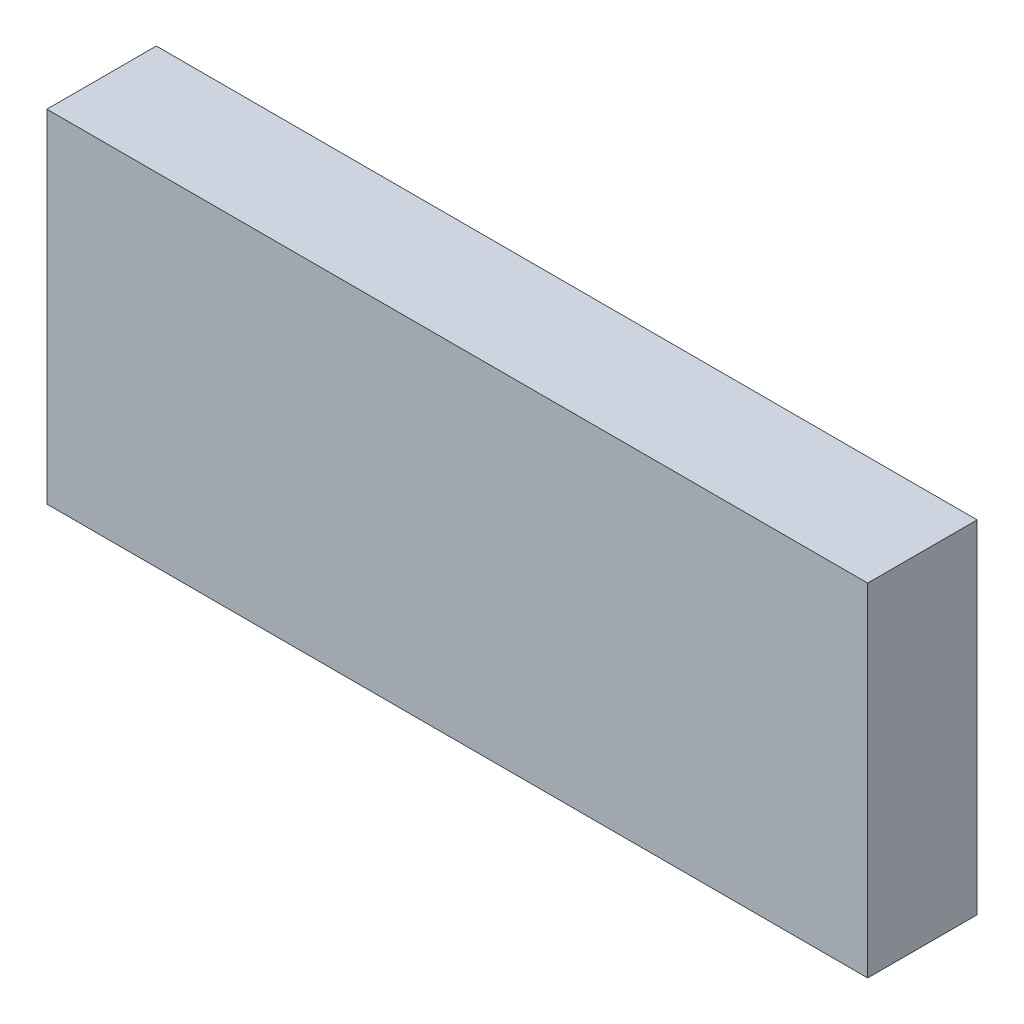
SolidWorks part; units mm, degrees
ref_plane "Front Plane" through (0, 0, 0) normal (0, 0, 1) x (1, 0, 0)
ref_plane "Top Plane" through (0, 0, 0) normal (0, 1, 0) x (1, 0, 0)
ref_plane "Right Plane" through (0, 0, 0) normal (1, 0, 0) x (0, 0, -1)
sketch "Sketch1" plane through (0, 0, 0) normal (0, 0, 1) x (1, 0, 0)
  line L1 (-90, -37.5) -> (90, -37.5)
  line L2 (-90, -37.5) -> (-90, 37.5)
  line L3 (-90, 37.5) -> (90, 37.5)
  line L4 (90, -37.5) -> (90, 37.5)
  line L5 (-90, -37.5) -> (90, 37.5) construction
  line L6 (-90, 37.5) -> (90, -37.5) construction
  point P0 (0, 0)
  dimension "D1" = 180
  dimension "D2" = 75
extrude "Boss-Extrude1" add sketch "Sketch1" along normal blind 24
sketch "Sketch2" plane through (0, 0, 24) normal (0, 0, 1) x (1, 0, 0)
  text T0 "BATTERY PACK" font "Century Gothic" height 10
